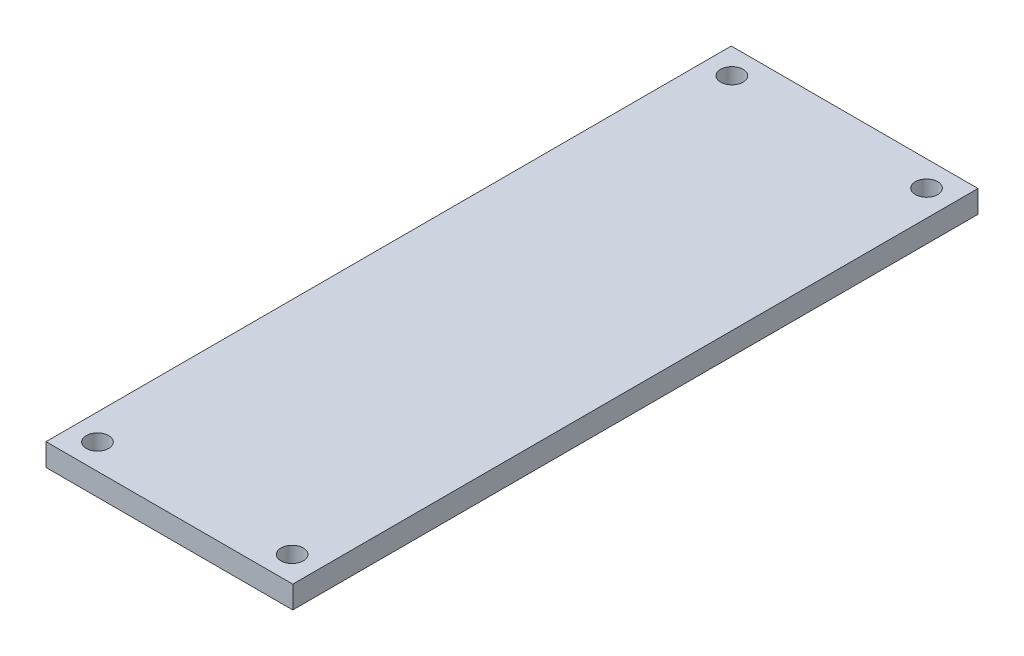
SolidWorks part; units mm, degrees
ref_plane "前视基准面" through (0, 0, 0) normal (0, 0, 1) x (1, 0, 0)
ref_plane "上视基准面" through (0, 0, 0) normal (0, 1, 0) x (1, 0, 0)
ref_plane "右视基准面" through (0, 0, 0) normal (1, 0, 0) x (0, 0, -1)
sketch "草图1" plane through (0, 0, 0) normal (0, 1, 0) x (1, 0, 0)
  line L1 (-16.525, 45.89) -> (16.525, 45.89)
  line L2 (-16.525, 45.89) -> (-16.525, -45.89)
  line L3 (-16.525, -45.89) -> (16.525, -45.89)
  line L4 (16.525, 45.89) -> (16.525, -45.89)
  line L5 (-16.525, 45.89) -> (16.525, -45.89) construction
  line L6 (-16.525, -45.89) -> (16.525, 45.89) construction
  point P0 (0, 0)
  dimension "D1" = 33.05
  dimension "D2" = 91.78
extrude "凸台-拉伸1" add sketch "草图1" along normal blind 3
sketch "草图2" plane through (0, 3, 0) normal (0, 1, 0) x (1, 0, 0)
  line L0 (0, -45.89) -> (0, 0) construction
  line L1 (-16.525, -45.89) -> (16.525, -45.89) construction
  line L2 (0, 0) -> (6.5484, 0) construction
  circle A0 centre (13.0377, -42.4856) radius 1.5
  circle A1 centre (-13.0377, -42.4856) radius 1.5
  circle A2 centre (-13.0377, 42.4856) radius 1.5
  circle A3 centre (13.0377, 42.4856) radius 1.5
  dimension "D1" = 3
extrude "切除-拉伸1" cut sketch "草图2" against normal blind 36.82
